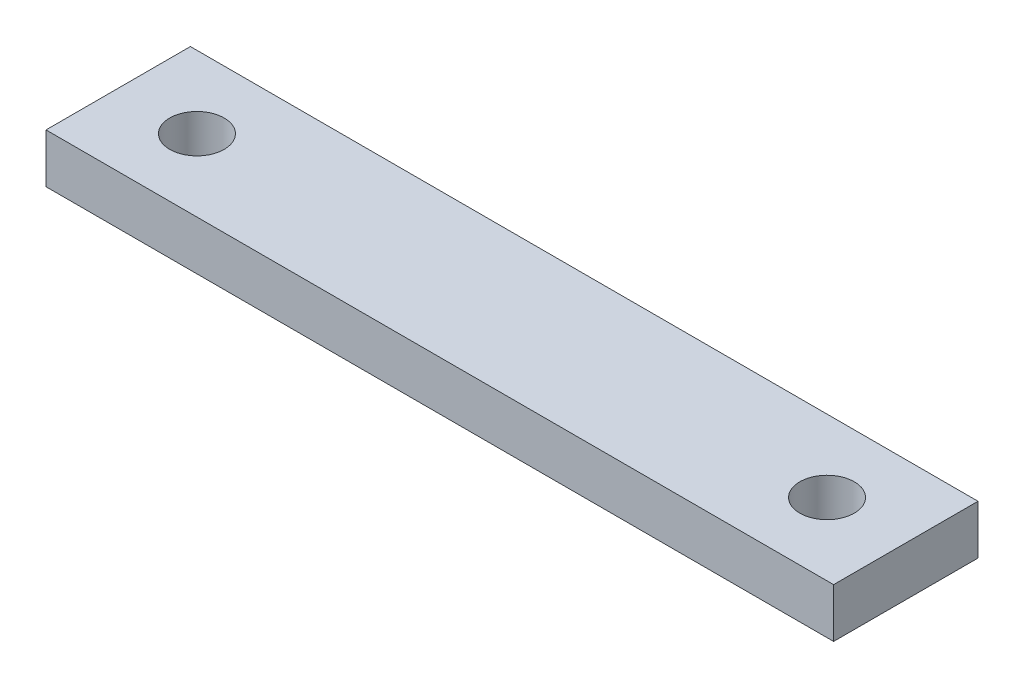
SolidWorks part; units mm, degrees
ref_plane "前视基准面" through (0, 0, 0) normal (0, 0, 1) x (1, 0, 0)
ref_plane "上视基准面" through (0, 0, 0) normal (0, 1, 0) x (1, 0, 0)
ref_plane "右视基准面" through (0, 0, 0) normal (1, 0, 0) x (0, 0, -1)
other "Configuration Table"
sketch "草图1" plane through (0, 0, 0) normal (0, 0, 1) x (1, 0, 0)
  line L0 (0, 0) -> (240, 0)
  line L1 (240, 0) -> (240, 15)
  line L2 (240, 15) -> (0, 15)
  line L3 (0, 15) -> (0, 0)
  dimension "width" = 240
  dimension "height" = 15
extrude "Top_beam" add sketch "草图1" along normal blind 44
sketch "草图2" plane through (0, 15, 0) normal (0, 1, 0) x (1, 0, 0)
  circle A0 centre (24, -22) radius 8.3
  dimension "diameter" = 16.6
  dimension "x" = 24
  dimension "y" = 22
extrude "Screw_passage" cut sketch "草图2" against normal through all
sketch "草图3" plane through (0, 15, 0) normal (0, 1, 0) x (1, 0, 0)
  circle A0 centre (216, -22) radius 8.3
  dimension "diameter" = 16.6
  dimension "x" = 216
  dimension "y" = 22
extrude "切除-拉伸2" cut sketch "草图3" against normal through all
